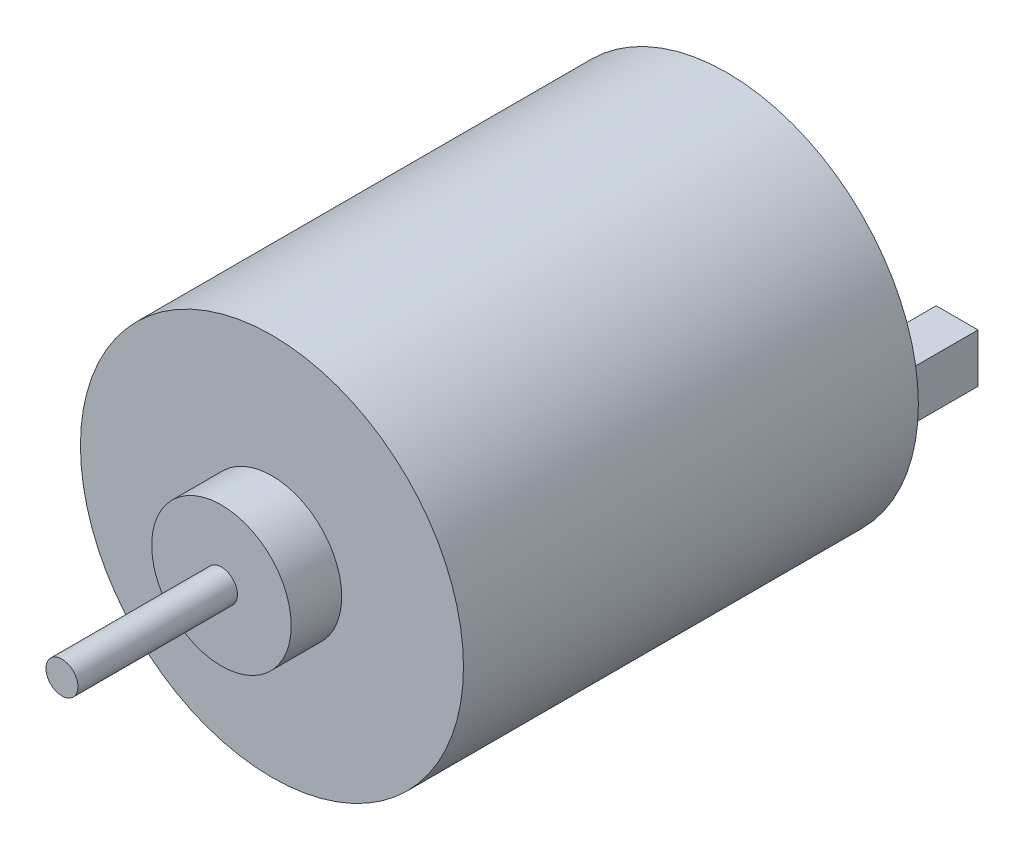
SolidWorks part; units mm, degrees
ref_plane "Front Plane" through (0, 0, 0) normal (0, 0, 1) x (1, 0, 0)
ref_plane "Top Plane" through (0, 0, 0) normal (0, 1, 0) x (1, 0, 0)
ref_plane "Right Plane" through (0, 0, 0) normal (1, 0, 0) x (0, 0, -1)
sketch "Sketch1" plane through (0, 0, 0) normal (0, 0, 1) x (1, 0, 0)
  circle A0 centre (0, 0) radius 13.725
  dimension "D1" = 27.45
extrude "Boss-Extrude1" add sketch "Sketch1" along normal blind 32.6
sketch "Sketch2" plane through (0, 0, 32.6) normal (0, 0, 1) x (1, 0, 0)
  circle A0 centre (0, 0) radius 5
  dimension "D1" = 10
extrude "Boss-Extrude2" add sketch "Sketch2" along normal blind 3.62
sketch "Sketch3" plane through (0, 0, 36.22) normal (0, 0, 1) x (1, 0, 0)
  circle A0 centre (0, 0) radius 1.145
  dimension "D1" = 2.29
extrude "Boss-Extrude3" add sketch "Sketch3" along normal blind 11.43
sketch "Sketch4" plane through (0, 0, 0) normal (0, 0, -1) x (-1, 0, 0)
  circle A0 centre (0, 0) radius 5
  dimension "D1" = 10
extrude "Boss-Extrude4" add sketch "Sketch4" along normal blind 2.15
sketch "Sketch5" plane through (0, 0, -2.15) normal (0, 0, -1) x (-1, 0, 0)
  circle A0 centre (0, 0) radius 1.15
  dimension "D1" = 2.3
extrude "Boss-Extrude5" add sketch "Sketch5" along normal blind 1
sketch "Sketch6" plane through (0, 0, 0) normal (0, 0, -1) x (-1, 0, 0)
  line L0 (-11.5, 0) -> (11.5, 0) construction
  line L2 (-13, 1.75) -> (-10, 1.75)
  line L3 (-13, 1.75) -> (-13, -1.75)
  line L4 (-13, -1.75) -> (-10, -1.75)
  line L5 (-10, 1.75) -> (-10, -1.75)
  line L6 (-13, 1.75) -> (-10, -1.75) construction
  line L7 (-13, -1.75) -> (-10, 1.75) construction
  line L8 (10, 1.75) -> (13, 1.75)
  line L9 (10, 1.75) -> (10, -1.75)
  line L10 (10, -1.75) -> (13, -1.75)
  line L11 (13, 1.75) -> (13, -1.75)
  line L12 (10, 1.75) -> (13, -1.75) construction
  line L13 (10, -1.75) -> (13, 1.75) construction
  point P6 (0, 0)
  dimension "D1" = 3.5
  dimension "D2" = 3
  dimension "D3" = 23
extrude "Boss-Extrude6" add sketch "Sketch6" along normal blind 5
